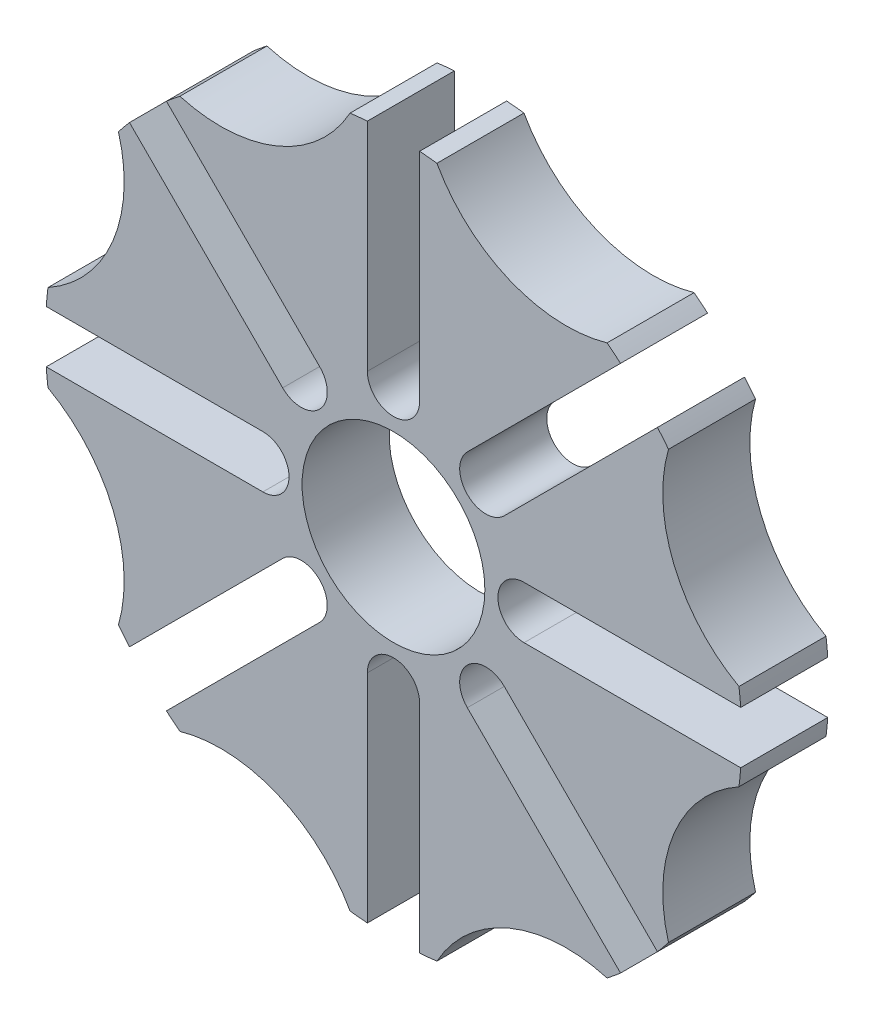
SolidWorks part; units mm, degrees
ref_plane "Front Plane" through (0, 0, 0) normal (0, 0, 1) x (1, 0, 0)
ref_plane "Top Plane" through (0, 0, 0) normal (0, 1, 0) x (1, 0, 0)
ref_plane "Right Plane" through (0, 0, 0) normal (1, 0, 0) x (0, 0, -1)
sketch "Sketch1" plane through (0, 0, 0) normal (0, 0, 1) x (1, 0, 0)
  line L0 (0, 0) -> (0, 12) construction
  line L1 (0, 0) -> (8.4853, 8.4853) construction
  line L4 (-3, 15) -> (-3, 39.8873)
  line L6 (3, 15) -> (3, 39.8873)
  line L9 (0, 15) -> (0, 37.3121) construction
  line L10 (8.4853, 12.7279) -> (26.0833, 30.3259)
  line L11 (12.7279, 8.4853) -> (30.3259, 26.0833)
  line L12 (15, 3) -> (39.8873, 3)
  line L13 (15, -3) -> (39.8873, -3)
  line L14 (12.7279, -8.4853) -> (30.3259, -26.0833)
  line L15 (8.4853, -12.7279) -> (26.0833, -30.3259)
  line L16 (3, -15) -> (3, -39.8873)
  line L17 (-3, -15) -> (-3, -39.8873)
  line L18 (-8.4853, -12.7279) -> (-26.0833, -30.3259)
  line L19 (-12.7279, -8.4853) -> (-30.3259, -26.0833)
  line L20 (-15, -3) -> (-39.8873, -3)
  line L21 (-15, 3) -> (-39.8873, 3)
  line L22 (-12.7279, 8.4853) -> (-30.3259, 26.0833)
  line L23 (-8.4853, 12.7279) -> (-26.0833, 30.3259)
  circle A1 centre (0, 0) radius 10.5
  arc A3 (-3, 15) -> (3, 15) centre (0, 15) ccw
  arc A5 (4.99, 39.6875) -> (24.5349, 31.5918) centre (19.8553, 47.935) ccw
  arc A6 (4.99, 39.6875) -> (3, 39.8873) centre (0, 0) ccw
  arc A7 (26.0833, 30.3259) -> (24.5349, 31.5918) centre (0, 0) ccw
  arc A8 (8.4853, 12.7279) -> (12.7279, 8.4853) centre (10.6066, 10.6066) ccw
  arc A9 (31.5918, 24.5349) -> (30.3259, 26.0833) centre (0, 0) ccw
  arc A10 (31.5918, 24.5349) -> (39.6875, 4.99) centre (47.935, 19.8553) ccw
  arc A11 (39.8873, 3) -> (39.6875, 4.99) centre (0, 0) ccw
  arc A12 (15, 3) -> (15, -3) centre (15, 0) ccw
  arc A13 (39.6875, -4.99) -> (39.8873, -3) centre (0, 0) ccw
  arc A14 (39.6875, -4.99) -> (31.5918, -24.5349) centre (47.935, -19.8553) ccw
  arc A15 (30.3259, -26.0833) -> (31.5918, -24.5349) centre (0, 0) ccw
  arc A16 (12.7279, -8.4853) -> (8.4853, -12.7279) centre (10.6066, -10.6066) ccw
  arc A17 (24.5349, -31.5918) -> (26.0833, -30.3259) centre (0, 0) ccw
  arc A18 (24.5349, -31.5918) -> (4.99, -39.6875) centre (19.8553, -47.935) ccw
  arc A19 (3, -39.8873) -> (4.99, -39.6875) centre (0, 0) ccw
  arc A20 (3, -15) -> (-3, -15) centre (0, -15) ccw
  arc A21 (-4.99, -39.6875) -> (-3, -39.8873) centre (0, 0) ccw
  arc A22 (-4.99, -39.6875) -> (-24.5349, -31.5918) centre (-19.8553, -47.935) ccw
  arc A23 (-26.0833, -30.3259) -> (-24.5349, -31.5918) centre (0, 0) ccw
  arc A24 (-8.4853, -12.7279) -> (-12.7279, -8.4853) centre (-10.6066, -10.6066) ccw
  arc A25 (-31.5918, -24.5349) -> (-30.3259, -26.0833) centre (0, 0) ccw
  arc A26 (-31.5918, -24.5349) -> (-39.6875, -4.99) centre (-47.935, -19.8553) ccw
  arc A27 (-39.8873, -3) -> (-39.6875, -4.99) centre (0, 0) ccw
  arc A28 (-15, -3) -> (-15, 3) centre (-15, 0) ccw
  arc A29 (-39.6875, 4.99) -> (-39.8873, 3) centre (0, 0) ccw
  arc A30 (-39.6875, 4.99) -> (-31.5918, 24.5349) centre (-47.935, 19.8553) ccw
  arc A31 (-30.3259, 26.0833) -> (-31.5918, 24.5349) centre (0, 0) ccw
  arc A32 (-12.7279, 8.4853) -> (-8.4853, 12.7279) centre (-10.6066, 10.6066) ccw
  arc A33 (-24.5349, 31.5918) -> (-26.0833, 30.3259) centre (0, 0) ccw
  arc A34 (-24.5349, 31.5918) -> (-4.99, 39.6875) centre (-19.8553, 47.935) ccw
  arc A35 (-3, 39.8873) -> (-4.99, 39.6875) centre (0, 0) ccw
  point P22 (0, 0)
  point P81 (0, 0)
  dimension "D2" = 8
  dimension "D3" = 21
  dimension "D5" = 6
  dimension "D10" = 17
  dimension "D4" = 45
  dimension "D6" = 6
  dimension "D8" = 2
  dimension "D9" = 2
extrude "Boss-Extrude1" add sketch "Sketch1" along normal mid plane 10
